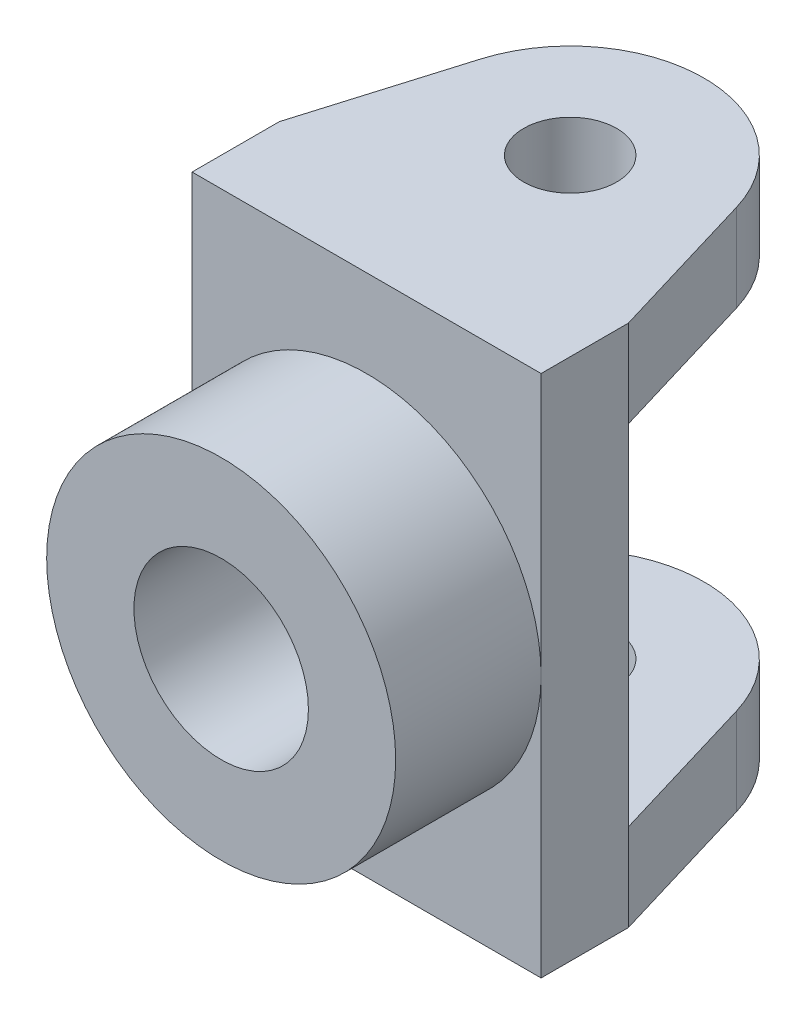
SolidWorks part; units mm, degrees
ref_plane "Front Plane" through (0, 0, 0) normal (0, 0, 1) x (1, 0, 0)
ref_plane "Top Plane" through (0, 0, 0) normal (0, 1, 0) x (1, 0, 0)
ref_plane "Right Plane" through (0, 0, 0) normal (1, 0, 0) x (0, 0, -1)
sketch "Sketch1" plane through (0, 0, 0) normal (0, 0, 1) x (1, 0, 0)
  line L1 (30, -45) -> (-30, -45)
  line L2 (30, -45) -> (30, 45)
  line L3 (30, 45) -> (-30, 45)
  line L4 (-30, -45) -> (-30, 45)
  line L5 (30, -45) -> (-30, 45) construction
  line L6 (30, 45) -> (-30, -45) construction
  point P0 (0, 0)
  dimension "D1" = 60
  dimension "D2" = 90
extrude "Boss-Extrude1" add sketch "Sketch1" along normal blind 15
sketch "Sketch2" plane through (0, 0, 15) normal (0, 0, 1) x (1, 0, 0)
  arc A0 (4, -14.4568) -> (-4, -14.4568) centre (0, 0) ccw
  circle A1 centre (0, 0) radius 30
  arc A2 (-4, -14.4568) -> (4, -14.4568) centre (0, 0) ccw
  dimension "D1" = 30
  dimension "D2" = 60
extrude "Boss-Extrude2" add sketch "Sketch2" along normal blind 25
sketch "Sketch3" plane through (0, 45, 0) normal (0, 1, 0) x (1, 0, 0)
  line L0 (-30, -15) -> (30, -15) construction
  line L1 (30, 0) -> (22.0329, 26.5993)
  line L2 (-30, 0) -> (-22.0329, 26.5993)
  line L3 (-30, 0) -> (30, 0)
  circle A0 centre (0, 20) radius 8
  arc A1 (22.0329, 26.5993) -> (-22.0329, 26.5993) centre (0, 20) ccw
  dimension "D1" = 46
  dimension "D2" = 16
  dimension "D3" = 35
extrude "Boss-Extrude3" add sketch "Sketch3" against normal blind 15
mirror "Mirror1" about plane through (0, 0, 0) normal (0, 1, 0) of "Boss-Extrude3"
